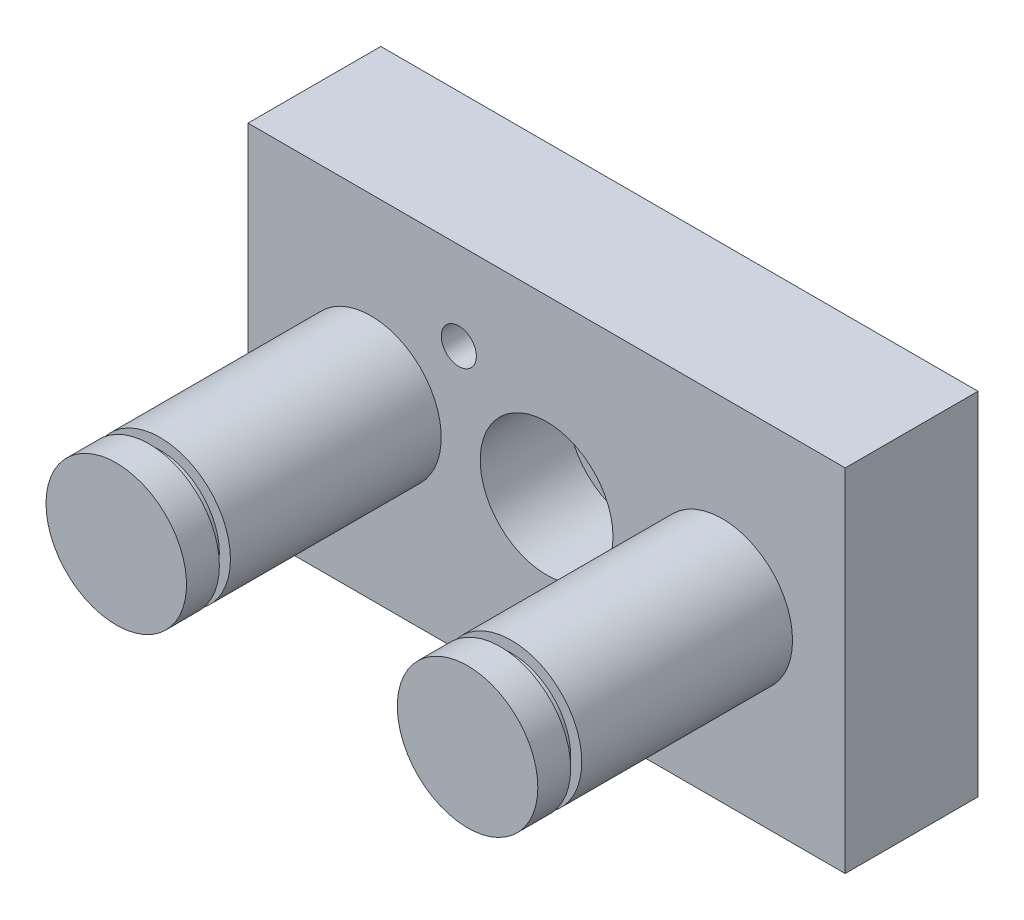
SolidWorks part; units mm, degrees
material "AISI 316 Barra de acero inoxidable recocido (SS)"
ref_plane "Alzado" through (0, 0, 0) normal (0, 0, 1) x (1, 0, 0)
ref_plane "Planta" through (0, 0, 0) normal (0, 1, 0) x (1, 0, 0)
ref_plane "Vista lateral" through (0, 0, 0) normal (1, 0, 0) x (0, 0, -1)
sketch "Croquis1" plane through (0, 0, 0) normal (0, 0, 1) x (1, 0, 0)
  line L1 (-26.9875, 15.875) -> (26.9875, 15.875)
  line L2 (-26.9875, 15.875) -> (-26.9875, -15.875)
  line L3 (-26.9875, -15.875) -> (26.9875, -15.875)
  line L4 (26.9875, 15.875) -> (26.9875, -15.875)
  line L5 (-26.9875, 15.875) -> (26.9875, -15.875) construction
  line L6 (-26.9875, -15.875) -> (26.9875, 15.875) construction
  point P0 (0, 0)
  dimension "D1" = 31.75
  dimension "D2" = 53.975
extrude "Saliente-Extruir1" add sketch "Croquis1" along normal blind 12
sketch "Croquis2" plane through (0, 0, 12) normal (0, 0, 1) x (1, 0, 0)
  circle A0 centre (0, 0) radius 3.969
  dimension "D1" = 7.938
extrude "Cortar-Extruir1" cut sketch "Croquis2" against normal through all
sketch "Croquis3" plane through (0, 0, 12) normal (0, 0, 1) x (1, 0, 0)
  circle A0 centre (0, 0) radius 6.0015
  dimension "D1" = 12.003
extrude "Cortar-Extruir2" cut sketch "Croquis3" against normal blind 7.938
sketch "Croquis4" plane through (0, 0, 12) normal (0, 0, 1) x (1, 0, 0)
  line L0 (12.266, -12.266) -> (-12.266, 12.266) construction
  line L1 (-12.266, -12.266) -> (12.266, 12.266) construction
  circle A0 centre (7.9375, -7.9375) radius 1.5875
  circle A1 centre (-7.9375, 7.9375) radius 1.5875
  dimension "D2" = 15.875
  dimension "D1" = 3.175
  dimension "D3" = 15.875
extrude "Cortar-Extruir3" cut sketch "Croquis4" against normal through all
sketch "Croquis5" plane through (0, 0, 12) normal (0, 0, 1) x (1, 0, 0)
  line L0 (-18.8989, 0) -> (20.1743, 0) construction
  line L1 (0, 0) -> (0, 13.0147) construction
  circle A0 centre (-15.875, 0) radius 3.969
  circle A1 centre (15.875, 0) radius 3.969
  dimension "D2" = 7.938
  dimension "D1" = 31.75
extrude "Cortar-Extruir4" cut sketch "Croquis5" against normal through all
sketch "Croquis6" plane through (0, 0, 0) normal (0, 1, 0) x (1, 0, 0)
  line L0 (-15.875, 0) -> (-15.875, -12) construction
  line L1 (-11.906, 0) -> (-19.844, 0) construction
  line L2 (-19.844, -12) -> (-11.906, -12) construction
  line L3 (-15.875, -1.191) -> (-15.875, -35.019)
  line L4 (-15.875, -35.019) -> (-9.525, -35.019)
  line L5 (-9.525, -35.019) -> (-9.525, -12)
  line L6 (-26.9875, -12) -> (26.9875, -12) construction
  line L7 (-9.525, -12) -> (-11.906, -12)
  line L8 (-11.906, -12) -> (-11.906, -1.191)
  line L9 (-11.906, -1.191) -> (-15.875, -1.191)
  dimension "D1" = 33.828
  dimension "D2" = 7.938
  dimension "D3" = 23.019
  dimension "D4" = 12.7
revolve "Revolución3" add sketch "Croquis6" angle 360 about L0
sketch "Croquis8" plane through (0, 0, 0) normal (0, 1, 0) x (1, 0, 0)
  line L0 (15.875, -12) -> (15.875, 2.1475) construction
  line L1 (11.906, -12) -> (19.844, -12) construction
  line L2 (15.875, -1.191) -> (15.875, -35.019)
  line L3 (15.875, -35.019) -> (9.525, -35.019)
  line L4 (9.525, -35.019) -> (9.525, -12)
  line L5 (6.35, -12) -> (9.525, -12) construction
  line L6 (9.525, -12) -> (11.906, -12)
  line L7 (-26.9875, -12) -> (26.9875, -12) construction
  line L8 (11.906, -12) -> (11.906, -1.191)
  line L9 (11.906, -1.191) -> (15.875, -1.191)
  dimension "D1" = 7.938
  dimension "D2" = 12.7
  dimension "D3" = 23.019
  dimension "D4" = 33.828
revolve "Revolución4" add sketch "Croquis8" angle 360 about L0
sketch "Croquis12" plane through (0, 0, 0) normal (0, 1, 0) x (1, 0, 0)
  line L0 (-9.525, -35.019) -> (-9.525, -12) construction
  line L1 (-9.525, -31.05) -> (-10.525, -31.05)
  line L2 (-10.525, -31.05) -> (-10.525, -32.05)
  line L3 (26.9875, -12) -> (-26.9875, -12) construction
  line L4 (-15.875, -35.019) -> (-15.875, -19.9416) construction
  line L5 (-22.225, -35.019) -> (-9.525, -35.019) construction
  line L6 (-10.525, -32.05) -> (-9.525, -32.05)
  line L7 (-9.525, -31.05) -> (-9.525, -32.05)
  dimension "D2" = 1
  dimension "D1" = 19.05
  dimension "D3" = 1
sketch "Croquis13" plane through (0, 0, 0) normal (0, 1, 0) x (1, 0, 0)
  line L0 (15.875, -35.019) -> (15.875, -17.7554) construction
  line L1 (9.525, -35.019) -> (22.225, -35.019) construction
  line L2 (22.225, -35.019) -> (22.225, -12) construction
  line L3 (26.9875, -12) -> (-26.9875, -12) construction
  line L4 (22.225, -31.05) -> (21.225, -31.05)
  line L5 (21.225, -31.05) -> (21.225, -32.05)
  line L6 (21.225, -32.05) -> (22.225, -32.05)
  line L7 (22.225, -32.05) -> (22.225, -31.05)
  dimension "D2" = 1
  dimension "D1" = 19.05
  dimension "D3" = 1
revolve "Cortar-Revolución3" cut sketch "Croquis12" angle 360 about L4
revolve "Cortar-Revolución4" cut sketch "Croquis13" angle 360 about L0
